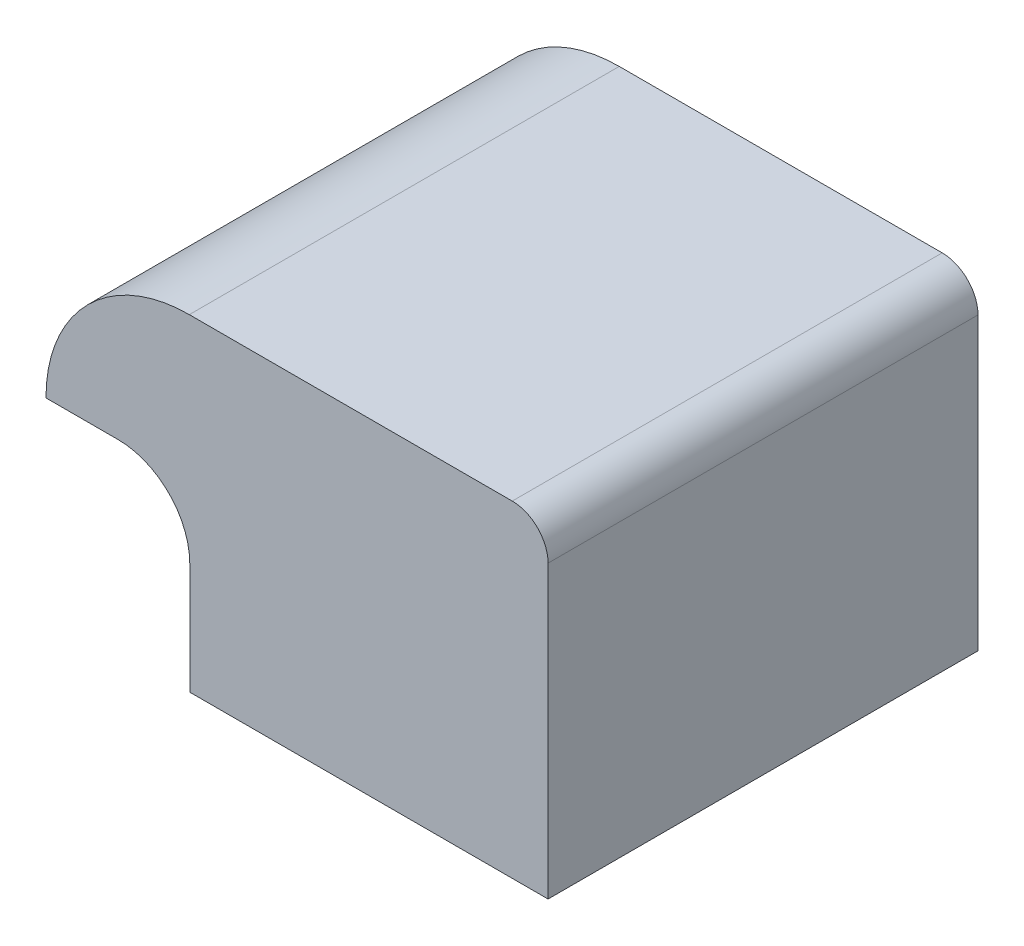
SolidWorks part; units mm, degrees
ref_plane "前基準面" through (0, 0, 0) normal (0, 0, 1) x (1, 0, 0)
ref_plane "上基準面" through (0, 0, 0) normal (0, 1, 0) x (1, 0, 0)
ref_plane "右基準面" through (0, 0, 0) normal (1, 0, 0) x (0, 0, -1)
sketch "草圖1" plane through (0, 0, 0) normal (0, 0, 1) x (1, 0, 0)
  line L0 (-48.7134, 0) -> (-41.7066, 0)
  line L1 (-41.7066, 0) -> (-41.7066, -4.56)
  line L2 (-48.7134, 0) -> (-48.7134, -2.0072)
  line L3 (-48.7134, -2.0072) -> (-46.7066, -2.0072)
  line L4 (-46.7066, -2.0072) -> (-46.7066, -4.56)
  line L5 (-46.7066, -4.56) -> (-41.7066, -4.56)
  point P7 (-43.4541, -2.6274)
  point P9 (0, 0)
  point P10 (-47.7735, -2.9642)
  point P12 (-43.7134, -4.56)
  point P13 (-46.7066, -2.0072)
  point P14 (-43.6613, -4.56)
  dimension "D1" = 4.56
  dimension "D2" = 5
extrude "填料-伸長1" add sketch "草圖1" along normal blind 6
fillet "圓角1" radius 0.5 1 edges at (-41.7066, 0, 3)
fillet "圓角2" radius 2 1 edges at (-48.7134, 0, 3)
fillet "圓角3" radius 1 1 edges at (-46.7066, -2.0072, 3)
